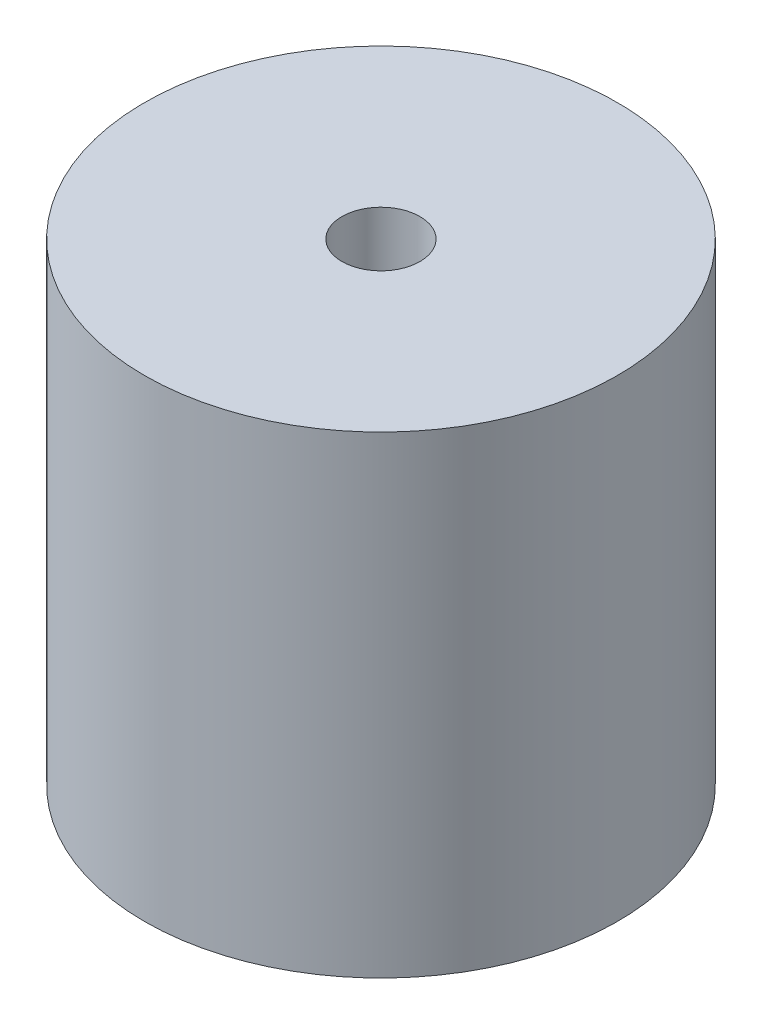
SolidWorks part; units mm, degrees
ref_plane "前视基准面" through (0, 0, 0) normal (0, 0, 1) x (1, 0, 0)
ref_plane "上视基准面" through (0, 0, 0) normal (0, 1, 0) x (1, 0, 0)
ref_plane "右视基准面" through (0, 0, 0) normal (1, 0, 0) x (0, 0, -1)
sketch "草图1" plane through (0, 0, 0) normal (0, 1, 0) x (1, 0, 0)
  circle A0 centre (0, 0) radius 100
  circle A1 centre (0, 0) radius 16.5
  dimension "D1" = 200
  dimension "D2" = 33
extrude "凸台-拉伸1" add sketch "草图1" along normal blind 200
